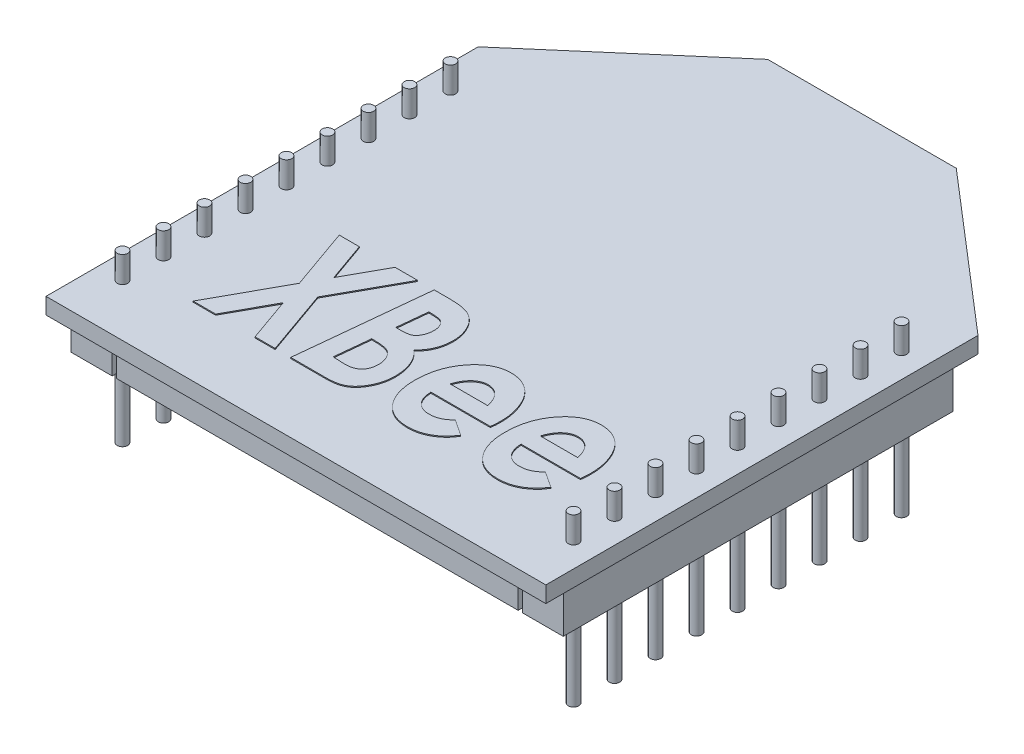
SolidWorks part; units mm, degrees
ref_plane "Front" through (0, 0, 0) normal (0, 0, 1) x (1, 0, 0)
ref_plane "Top" through (0, 0, 0) normal (0, 1, 0) x (1, 0, 0)
ref_plane "Right" through (0, 0, 0) normal (1, 0, 0) x (0, 0, -1)
sketch "Sketch1" plane through (0, 0, 0) normal (0, 1, 0) x (1, 0, 0)
  line L0 (0, 0) -> (0, 21.08)
  line L1 (0, 0) -> (24.38, 0)
  line L3 (0, 21.08) -> (7.59, 27.61)
  line L4 (24.38, 21.08) -> (16.79, 27.61)
  line L5 (24.38, 0) -> (24.38, 21.08)
  line L6 (7.59, 27.61) -> (16.79, 27.61)
extrude "Boss-Extrude2" add sketch "Sketch1" along normal blind 0.79
sketch "Sketch3" plane through (0, 0, 0) normal (0, -1, 0) x (1, 0, 0)
  line L0 (22.19, -1.04) -> (22.19, -20.04)
  line L2 (24.19, -1.04) -> (24.19, -20.04)
  line L3 (24.19, -1.04) -> (22.19, -1.04)
  line L4 (24.19, -20.04) -> (22.19, -20.04)
  line L7 (0.19, -20.04) -> (2.19, -20.04)
  line L8 (0.19, -1.04) -> (2.19, -1.04)
  line L9 (0.19, -1.04) -> (0.19, -20.04)
  line L10 (2.19, -1.04) -> (2.19, -20.04)
  line L13 (2.39, -1.04) -> (21.99, -1.04)
  line L14 (2.39, -1.04) -> (2.39, -20.04)
  line L15 (2.39, -20.04) -> (21.99, -20.04)
  line L16 (21.99, -1.04) -> (21.99, -20.04)
extrude "Boss-Extrude3" add sketch "Sketch3" along normal blind 2
sketch "Sketch4" plane through (0, 0.79, 0) normal (0, 1, 0) x (1, 0, 0)
  circle A0 centre (1.19, 10.54) radius 0.255
  circle A1 centre (1.19, 12.54) radius 0.255
  circle A2 centre (1.19, 14.54) radius 0.255
  circle A3 centre (1.19, 16.54) radius 0.255
  circle A4 centre (1.19, 18.54) radius 0.255
  circle A5 centre (1.19, 8.54) radius 0.255
  circle A6 centre (1.19, 6.54) radius 0.255
  circle A7 centre (1.19, 4.54) radius 0.255
  circle A8 centre (1.19, 2.54) radius 0.255
  circle A9 centre (23.19, 2.54) radius 0.255
  circle A10 centre (23.19, 4.54) radius 0.255
  circle A11 centre (23.19, 6.54) radius 0.255
  circle A12 centre (23.19, 8.54) radius 0.255
  circle A13 centre (23.19, 18.54) radius 0.255
  circle A14 centre (23.19, 16.54) radius 0.255
  circle A15 centre (23.19, 14.54) radius 0.255
  circle A16 centre (23.19, 12.54) radius 0.255
  circle A17 centre (23.19, 10.54) radius 0.255
  dimension "D1" = 5
  dimension "D2" = 5
extrude "Boss-Extrude4" add sketch "Sketch4" along normal blind 1.27 and the other way blind 6.85 separate body
sketch "Sketch6" plane through (0, 0.79, 0) normal (0, 1, 0) x (1, 0, 0)
  text T0 "<b><i>XBee</i></b>" font "Century Gothic" height 6.35
extrude "Boss-Extrude8" add sketch "Sketch6" along normal blind 0.05 separate body
